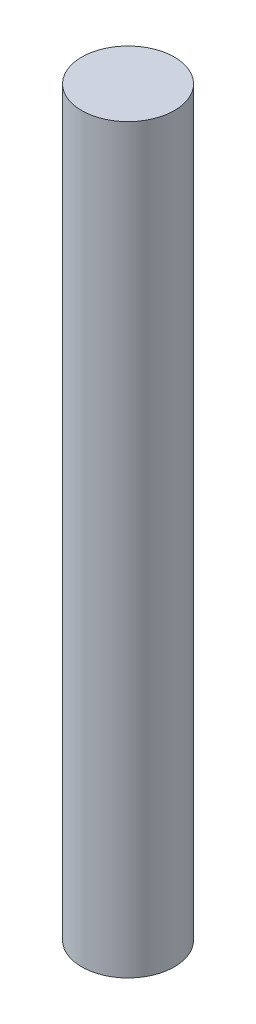
SolidWorks part; units mm, degrees
ref_plane "Front" through (0, 0, 0) normal (0, 0, 1) x (1, 0, 0)
ref_plane "Top" through (0, 0, 0) normal (0, 1, 0) x (1, 0, 0)
ref_plane "Right" through (0, 0, 0) normal (1, 0, 0) x (0, 0, -1)
sketch "Sketch1" plane through (0, 0, 0) normal (0, 1, 0) x (1, 0, 0)
  circle A0 centre (0, 0) radius 2.3813
  dimension "D1" = 4.7625
extrude "Boss-Extrude1" add sketch "Sketch1" along normal mid plane 38.1 contours A0
